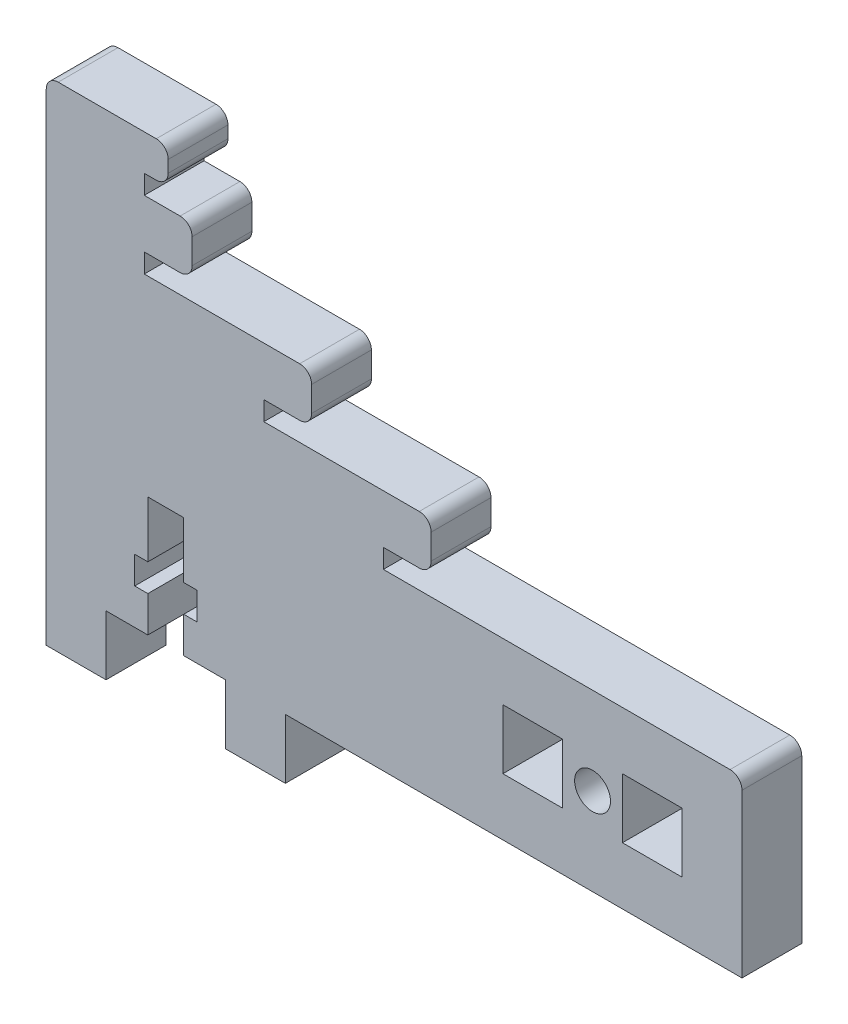
SolidWorks part; units mm, degrees
ref_plane "Front Plane" through (0, 0, 0) normal (0, 0, 1) x (1, 0, 0)
ref_plane "Top Plane" through (0, 0, 0) normal (0, 1, 0) x (1, 0, 0)
ref_plane "Right Plane" through (0, 0, 0) normal (1, 0, 0) x (0, 0, -1)
sketch "Sketch1" plane through (0, 0, 0) normal (0, 0, 1) x (1, 0, 0)
  line L0 (0, 5) -> (0, 19.9828)
  line L1 (20, 5) -> (20, 19.6) construction
  line L3 (28.2, 19.6) -> (28.2, 21.2)
  line L4 (28.2, 21.2) -> (32.2, 21.2)
  line L5 (32.2, 21.2) -> (32.2, 25.3)
  line L7 (0, 25.3) -> (0, 19.9828)
  line L8 (10, 5) -> (10, 15.0197) construction
  line L9 (8.5, 5) -> (5, 5)
  line L10 (5, 0) -> (0, 0)
  line L11 (0, 0) -> (0, 5)
  line L12 (5, 0) -> (5, 5)
  line L13 (11.5, 5) -> (15, 5)
  line L14 (15, 5) -> (15, 0)
  line L15 (15, 0) -> (20, 0)
  line L16 (20, 0) -> (20, 5)
  line L17 (8.5, 5) -> (11.5, 5) construction
  line L18 (11.5, 5) -> (11.5, 8)
  line L19 (11.5, 10.3) -> (12.6, 10.3)
  line L20 (7.4, 8) -> (7.4, 10.3)
  line L21 (12.6, 8) -> (11.5, 8)
  line L22 (11.5, 10.3) -> (11.5, 15)
  line L23 (11.5, 15) -> (8.5, 15)
  line L24 (8.5, 15) -> (8.5, 10.3)
  line L25 (8.5, 8) -> (7.4, 8)
  line L26 (12.6, 10.3) -> (12.6, 8)
  line L27 (7.4, 10.3) -> (8.5, 10.3)
  line L28 (8.5, 8) -> (8.5, 5)
  line L29 (10, 15) -> (10, 5) construction
  line L30 (32.2, 25.3) -> (18.2, 25.3)
  line L31 (18.2, 25.3) -> (18.2, 26.9)
  line L32 (18.2, 26.9) -> (22.2, 26.9)
  line L33 (22.2, 26.9) -> (22.2, 31)
  line L35 (0, 30.1) -> (0, 25.3)
  line L37 (58.2, 19.6) -> (58.2, 5)
  line L38 (58.2, 5) -> (20, 5)
  line L39 (22.2, 31) -> (8.2, 31)
  line L40 (8.2, 31) -> (8.2, 32.6)
  line L41 (8.2, 32.6) -> (12.2, 32.6)
  line L47 (10.2, 41.3) -> (0, 41.3)
  line L48 (0, 41.3) -> (0, 30.1)
  line L49 (12.2, 32.6) -> (12.2, 36.7)
  line L50 (12.2, 36.7) -> (8.2, 36.7)
  line L51 (8.2, 36.7) -> (8.2, 38.3)
  line L52 (8.2, 38.3) -> (10.2, 38.3)
  line L53 (10.2, 38.3) -> (10.2, 41.3)
  line L54 (28.2, 19.6) -> (58.2, 19.6)
  line L55 (58.2, 12.3) -> (32.0391, 12.3) construction
  point P41 (8.2, 37.5)
  line B0 (43.2, 12.3) -> (48.2, 12.3) construction
  line B1 (43.2, 14.8) -> (38.2, 14.8)
  line B2 (43.2, 14.8) -> (43.2, 9.8)
  line B3 (43.2, 9.8) -> (38.2, 9.8)
  line B4 (38.2, 14.8) -> (38.2, 9.8)
  line B5 (48.2, 14.8) -> (53.2, 14.8)
  line B6 (48.2, 14.8) -> (48.2, 9.8)
  line B7 (48.2, 9.8) -> (53.2, 9.8)
  line B8 (53.2, 14.8) -> (53.2, 9.8)
  circle B9 centre (45.7, 12.3) radius 1.5
  dimension "D2" = 14.6
  dimension "D3" = 4
  dimension "D4" = 5.7
  dimension "D5" = 10
  dimension "D6" = 5
  dimension "D7" = 5
  dimension "D8" = 5.2
  dimension "D9" = 3
  dimension "D10" = 2.3
  dimension "D11" = 3
  dimension "D12" = 10
  dimension "D13" = 8.2
  dimension "D14" = 10
  dimension "D15" = 2
  dimension "D16" = 1.6
  dimension "D17" = 10
  dimension "D18" = 5.7
  dimension "D19" = 3
  dimension "D20" = 5
  dimension "D21" = 10
  dimension "D22" = 5.7
sketch_block_instance "Trou M3 plots 5mm Ecartement Reduit-3"
sketch_block "Trou M3 plots 5mm Ecartement Reduit" parameters "D2"=3, "D1"=5, "D3"=5, "D4"=5
extrude "Boss-Extrude1" add sketch "Sketch1" along normal blind 5
fillet "Fillet3" radius 1 10 edges at (32.2, 21.2, 2.5) (58.2, 19.6, 2.5) (0, 41.3, 2.5) (10.2, 38.3, 2.5) (10.2, 41.3, 2.5) (12.2, 32.6, 2.5) (12.2, 36.7, 2.5) (22.2, 26.9, 2.5) (22.2, 31, 2.5) (32.2, 25.3, 2.5)
